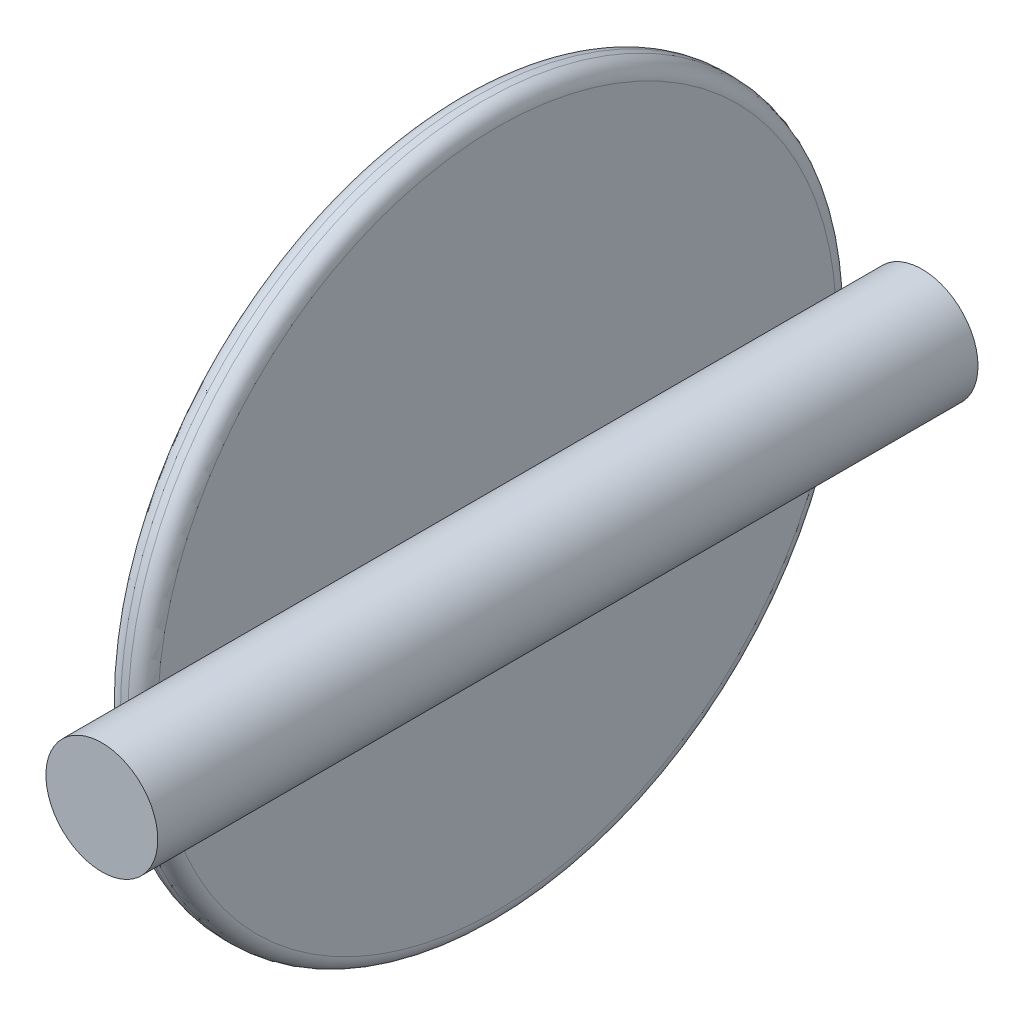
SolidWorks part; units mm, degrees
material "Plain Carbon Steel"
ref_plane "Front Plane" through (0, 0, 0) normal (0, 0, 1) x (1, 0, 0)
ref_plane "Top Plane" through (0, 0, 0) normal (0, 1, 0) x (1, 0, 0)
ref_plane "Right Plane" through (0, 0, 0) normal (1, 0, 0) x (0, 0, -1)
sketch "Sketch1" plane through (0, 0, 0) normal (1, 0, 0) x (0, 0, -1)
  circle A0 centre (0, 0) radius 47.5
  dimension "D1" = 95
extrude "Boss-Extrude1" add sketch "Sketch1" along normal blind 5
fillet "Fillet1" radius 2 2 edges at (0, 0, -47.5) (5, 0, -47.5)
sketch "Sketch2" plane through (0, 0, 0) normal (0, 0, 1) x (1, 0, 0)
  circle A0 centre (12, 0) radius 7.5
  point P2 (0, 0)
  dimension "D1" = 15
  dimension "D2" = 12
extrude "Boss-Extrude2" add sketch "Sketch2" along normal blind 60 and the other way blind 50
